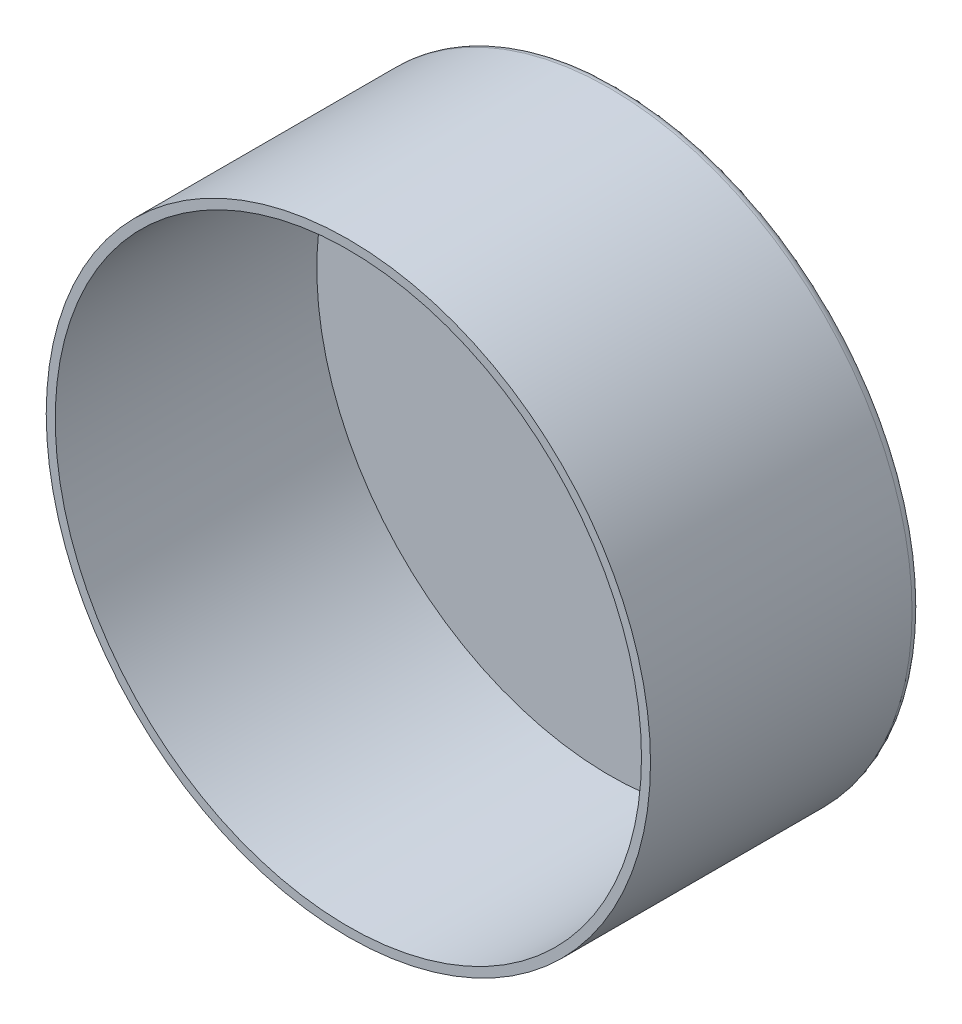
SolidWorks part; units mm, degrees
ref_plane "Front Plane" through (0, 0, 0) normal (0, 0, 1) x (1, 0, 0)
ref_plane "Top Plane" through (0, 0, 0) normal (0, 1, 0) x (1, 0, 0)
ref_plane "Right Plane" through (0, 0, 0) normal (1, 0, 0) x (0, 0, -1)
sketch "Sketch1" plane through (0, 0, 0) normal (0, 0, 1) x (1, 0, 0)
  circle A0 centre (0, 0) radius 16.75
  dimension "D1" = 33.5
extrude "Boss-Extrude1" add sketch "Sketch1" along normal blind 15
shell "Shell2" thickness 0.5
fillet "Fillet1" radius 0.5 1 edges at (16.75, 0, 0)
